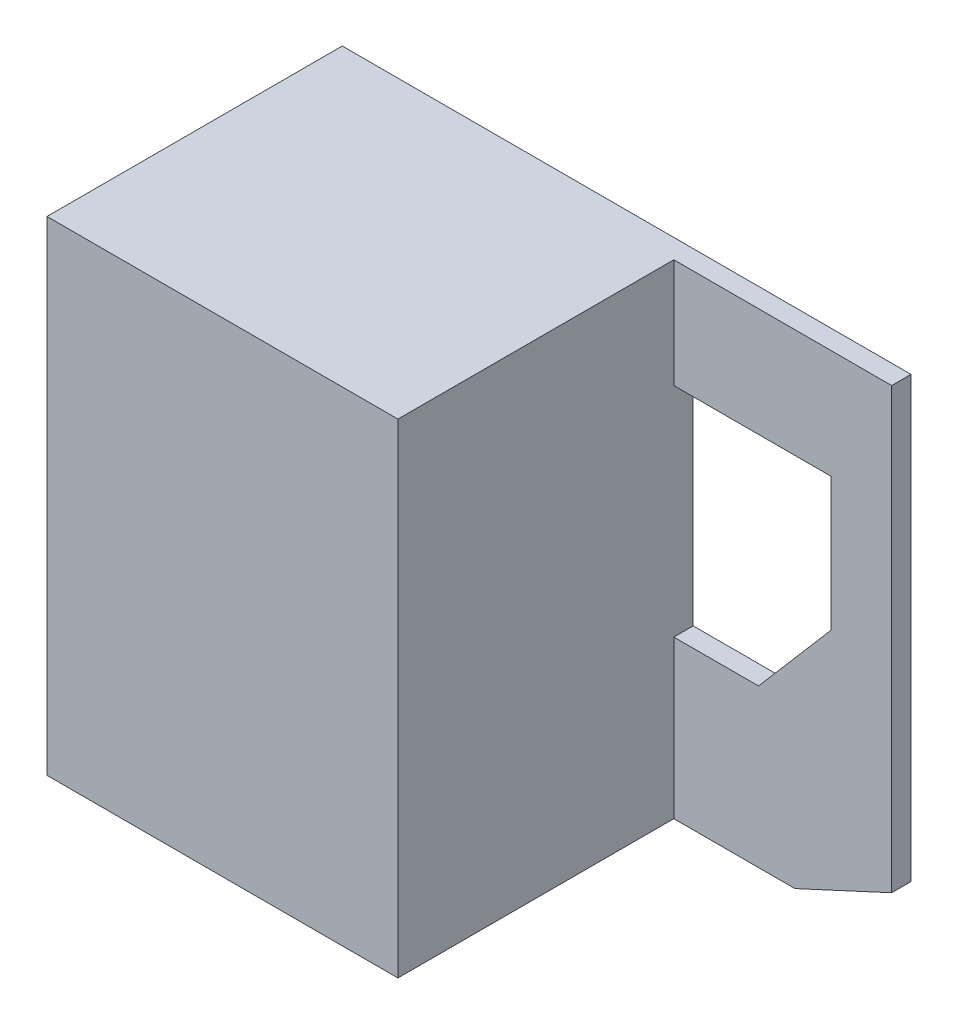
SolidWorks part; units mm, degrees
ref_plane "Alzado" through (0, 0, 0) normal (0, 0, 1) x (1, 0, 0)
ref_plane "Planta" through (0, 0, 0) normal (0, 1, 0) x (1, 0, 0)
ref_plane "Vista lateral" through (0, 0, 0) normal (1, 0, 0) x (0, 0, -1)
sketch "Croquis1" plane through (0, 0, 0) normal (0, 0, 1) x (1, 0, 0)
  line L1 (-14.5, -20) -> (14.5, -20)
  line L2 (-14.5, -20) -> (-14.5, 20)
  line L3 (-14.5, 20) -> (14.5, 20)
  line L4 (14.5, -20) -> (14.5, 20)
  line L5 (-14.5, -20) -> (14.5, 20) construction
  line L6 (-14.5, 20) -> (14.5, -20) construction
  point P0 (0, 0)
  dimension "D1" = 40
  dimension "D2" = 29
extrude "Saliente-Extruir1" add sketch "Croquis1" along normal blind 24.4
sketch "Croquis2" plane through (0, 0, 0) normal (0, 0, 1) x (1, 0, 0)
  line L0 (14.5, 20) -> (32.5, 20)
  line L1 (32.5, 20) -> (32.5, -16.3)
  line L2 (32.5, -16.3) -> (24.5, -20)
  line L3 (24.5, -20) -> (14.5, -20)
  line L4 (14.5, -20) -> (14.5, 20) construction
  line L5 (14.5, -20) -> (14.5, -7)
  line L6 (-14.5, -20) -> (14.5, -20) construction
  line L7 (14.5, 11) -> (27.5, 11)
  line L8 (27.5, 11) -> (27.5, 0)
  line L9 (27.5, 0) -> (21.5, -7)
  line L10 (21.5, -7) -> (14.5, -7)
  line L11 (14.5, 11) -> (14.5, 20)
  dimension "D1" = 18
  dimension "D2" = 3.7
  dimension "D3" = 8
  dimension "D4" = 9
  dimension "D5" = 13
  dimension "D6" = 5
  dimension "D7" = 7
  dimension "D8" = 6
extrude "Saliente-Extruir2" add sketch "Croquis2" along normal blind 1.6
sketch "Croquis3" plane through (0, -20, 0) normal (0, -1, 0) x (1, 0, 0)
  line L0 (14.5, 24.4) -> (14.5, 1.6) construction
  circle A0 centre (0, 13) radius 5
  point P7 (14.5, 13)
  dimension "D1" = 10
extrude "Cortar-Extruir1" cut sketch "Croquis3" against normal blind 34
